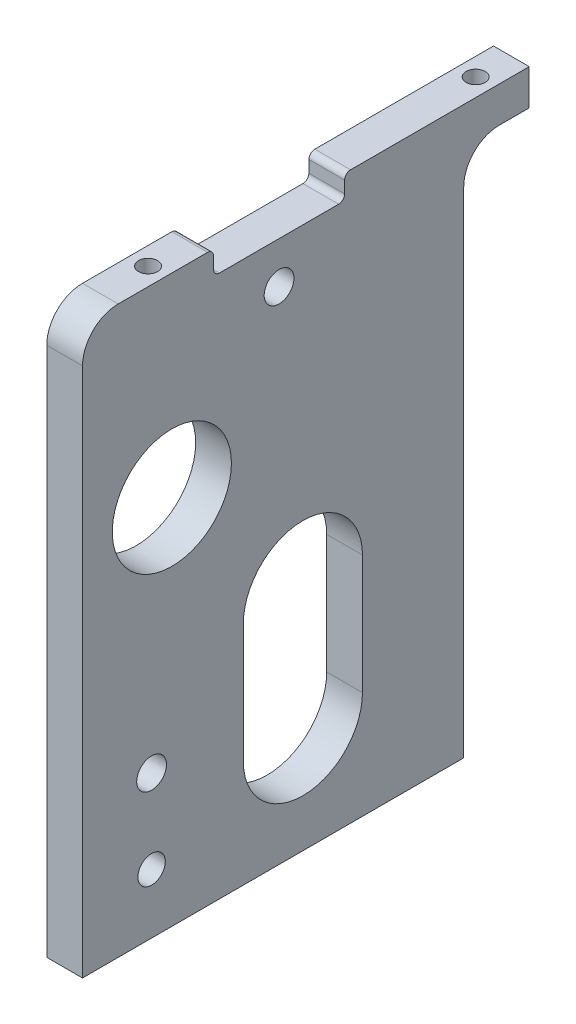
SolidWorks part; units mm, degrees
material "6063-T5"
ref_plane "Front Plane" through (0, 0, 0) normal (0, 0, 1) x (1, 0, 0)
ref_plane "Top Plane" through (0, 0, 0) normal (0, 1, 0) x (1, 0, 0)
ref_plane "Right Plane" through (0, 0, 0) normal (1, 0, 0) x (0, 0, -1)
sketch "Sketch1" plane through (0, 0, 0) normal (1, 0, 0) x (0, 0, -1)
  line L0 (-15.5, -23.75) -> (22, -23.75) construction
  line L1 (22, -23.75) -> (22, 16.25) construction
  line L2 (15.5, 23.75) -> (-15.5, 23.75) construction
  line L3 (-15.5, 23.75) -> (-15.5, -23.75) construction
  line L4 (55, 0) -> (-55, 0) construction
  line L5 (2, -4.75) -> (2, -14.75) construction
  line L6 (7, -4.75) -> (7, -14.75)
  line L7 (-3, -4.75) -> (-3, -14.75)
  line L8 (0, 55) -> (0, -55) construction
  line L9 (-15.5, 23.75) -> (15.5, 23.75)
  line L10 (15.5, 8.25) -> (15.5, -23.75)
  line L11 (-15.5, -23.75) -> (15.5, -23.75)
  line L12 (22, 23.75) -> (22, 16.25) construction
  line L13 (15.5, 8.25) -> (15.5, 20.75)
  line L14 (22, 23.75) -> (15.5, 23.75) construction
  line L15 (15.5, 23.75) -> (22, 23.75) construction
  line L16 (22, 16.25) -> (22, 23.75) construction
  line L17 (15.5, 23.75) -> (21, 23.75)
  line L18 (21, 23.75) -> (21, 20.75)
  line L19 (21, 20.75) -> (15.5, 20.75)
  line L20 (15.5, 20.75) -> (15.5, 23.75) construction
  line L21 (-15.5, -23.75) -> (-16.5, -23.75)
  line L28 (-16.5, -23.75) -> (-16.5, 23.75)
  line L29 (-16.5, 23.75) -> (-15.5, 23.75)
  arc A0 (7, -4.75) -> (-3, -4.75) centre (2, -4.75) ccw
  arc A1 (-3, -14.75) -> (7, -14.75) centre (2, -14.75) ccw
  arc A3 (15.5, 8.25) -> (18, 12.25) centre (21.4284, 7.326) cw construction
  arc A4 (18, 12.25) -> (22, 16.25) centre (16.2583, 17.9917) ccw construction
  circle A5 centre (-9, 7.422) radius 5
  circle A6 centre (-10.7, -18.75) radius 1.15
  point P2 (0, 23.75)
  point P5 (-15.5, 0)
  point P11 (2, -9.75)
  dimension "D12" = 6
  dimension "D14" = 10
  dimension "D21" = 2.3
  dimension "D1" = 47.5
  dimension "D2" = 37.5
  dimension "D3" = 10
  dimension "D4" = 10
  dimension "D5" = 0
  dimension "D7" = 17.5
  dimension "D8" = 31
  dimension "D9" = 8
  dimension "D10" = 4
  dimension "D11" = 2.5
  dimension "D13" = 32
  dimension "D15" = 31.172
  dimension "D16" = 6.5
  dimension "D6" = 19
  dimension "D17" = 5.5
  dimension "D18" = 3
  dimension "D19" = 4.8
  dimension "D20" = 5
  dimension "D24" = 1
extrude "Boss-Extrude1" add sketch "Sketch1" along normal mid plane 3
sketch "Sketch2" plane through (-1.5, 0, 0) normal (-1, 0, 0) x (0, 0, 1)
  line L0 (-21, 23.75) -> (16.5, 23.75) construction
  line L1 (5.5, 23.75) -> (12.5, 23.75)
  line L2 (5.5, 23.75) -> (5.5, 20.75)
  line L3 (5.5, 20.75) -> (12.5, 20.75)
  line L4 (12.5, 23.75) -> (12.5, 20.75)
  line L10 (16.5, 23.75) -> (16.5, -23.75) construction
  line L11 (-21, 23.75) -> (-14, 23.75)
  line L12 (-21, 23.75) -> (-21, 20.75)
  line L13 (-21, 20.75) -> (-14, 20.75)
  line L14 (-14, 23.75) -> (-14, 20.75)
  dimension "D1" = 4
  dimension "D2" = 3
  dimension "D3" = 7
extrude "Boss-Extrude2" [suppressed] add sketch "Sketch2" along normal blind 8
sketch "Sketch3" [suppressed] plane through (0, 20.75, 0) normal (0, 1, 0) x (1, 0, 0)
  line L0 (-1.5, -5.5) -> (-1.5, -12.5) construction
  line L7 (-5, 20.0981) -> (-7.25, 18.799)
  line L8 (-7.25, 18.799) -> (-7.25, 16.201)
  line L9 (-7.25, 16.201) -> (-5, 14.9019)
  line L10 (-5, 14.9019) -> (-2.75, 16.201)
  line L11 (-2.75, 16.201) -> (-2.75, 18.799)
  line L12 (-2.75, 18.799) -> (-5, 20.0981)
  line L13 (1.5, -16.5) -> (-1.5, -16.5) construction
  line L14 (-1.5, 15.5) -> (-1.5, 14) construction
  line L15 (1.5, 15.5) -> (-1.5, 15.5) construction
  line L16 (-9.5, -5.5) -> (-9.5, -12.5) construction
  line L18 (-7.25, -7.701) -> (-7.25, -10.299)
  line L19 (-7.25, -10.299) -> (-5, -11.5981)
  line L20 (-5, -11.5981) -> (-2.75, -10.299)
  line L21 (-2.75, -10.299) -> (-2.75, -7.701)
  line L22 (-2.75, -7.701) -> (-5, -6.4019)
  line L23 (-5, -6.4019) -> (-7.25, -7.701)
  circle A0 centre (-5, -9) radius 2.25 construction
  circle A1 centre (-5, 17.5) radius 2.25 construction
  dimension "D1" = 4.5
  dimension "D2" = 3.5
  dimension "D3" = 7.5
  dimension "D4" = 2
  dimension "D5" = 3.5
extrude "Cut-Extrude1" [suppressed] cut sketch "Sketch3" along normal blind 2
fillet "Fillet1" radius 3 2 edges at (0, 20.75, -15.5) (0, 23.75, 16.5)
hole_wizard "M2 Clearance Hole1" [suppressed] positions "Sketch4" profile "Sketch5" hole size "M2" standard "ISO"
sketch "Sketch4" [suppressed] plane through (0, 22.75, 0) normal (0, -1, 0) x (-1, 0, 0)
  line L4 (1.5, 18.5) -> (1.5, 14) construction
  line L5 (1.5, -5.5) -> (1.5, -12.5) construction
  line L6 (1.5, 15.5) -> (-1.5, 15.5) construction
  line L8 (-1.5, -16.5) -> (1.5, -16.5) construction
  point P0 (5, -9)
  point P13 (5, 17.5)
  dimension "D1" = 3.5
  dimension "D3" = 3.5
  dimension "D2" = 2
  dimension "D4" = 7.5
sketch "Sketch5" plane through (-5, 22.75, 9) normal (1, 0, 0) x (0, 0, -1)
  line L0 (0, 0) -> (0, 8.9811)
  line L1 (0, 8.9811) -> (1.3, 8.2)
  line L2 (1.3, 8.2) -> (1.3, 0)
  line L5 (1.3, 0) -> (0, 0)
  line L10 (0, 8.9811) -> (-1.3, 8.2) construction
  line L11 (0, -6.35) -> (0, 107.95) construction
  dimension "Hole Dia." = 2.6
  dimension "Hole Depth" = 8.2
  dimension "Drill Angle" = 118
fillet "Fillet2" [suppressed] radius 1.5
hole_wizard "Tap Drill for M2 Tap1" positions "Sketch6" profile "Sketch7" hole size "M2" standard "ISO"
sketch "Sketch6" plane through (0, 23.75, 0) normal (0, 1, 0) x (1, 0, 0)
  line L0 (1.5, 21) -> (-1.5, 21) construction
  line L1 (1.5, 21) -> (1.5, -13.5) construction
  point P0 (0, -9.5)
  point P2 (0, 18)
  dimension "D1" = 3
  dimension "D2" = 1.5
  dimension "D3" = 27.5
sketch "Sketch7" plane through (0, 23.75, 9.5) normal (1, 0, 0) x (0, 0, 1)
  line L0 (0, 0) -> (0, 6.4807)
  line L1 (0, 6.4807) -> (0.8, 6)
  line L2 (0.8, 6) -> (0.8, 0)
  line L5 (0.8, 0) -> (0, 0)
  line L10 (0, 6.4807) -> (-0.8, 6) construction
  line L11 (0, -6.35) -> (0, 107.95) construction
  dimension "Hole Dia." = 1.6
  dimension "Hole Depth" = 6
  dimension "Drill Angle" = 118
cosmetic thread "Cosmetic Thread1" parameters "D2"=2
cosmetic thread "Cosmetic Thread2" parameters "D2"=2
hole_wizard "Tap Drill for M3 Tap1" positions "Sketch8" profile "Sketch9" hole size "M3" standard "ISO" end condition through all
sketch "Sketch8" plane through (1.5, 0, 0) normal (1, 0, 0) x (0, 0, -1)
  line L0 (-16.5, -23.75) -> (15.5, -23.75) construction
  line L1 (21, 23.75) -> (-13.5, 23.75) construction
  line L2 (-16.5, 20.75) -> (-16.5, -23.75) construction
  point P0 (-10.7, -11.75)
  point P2 (0, 18.25)
  dimension "D1" = 12
  dimension "D2" = 5.5
  dimension "D3" = 5.8
  dimension "D4" = 16.5
sketch "Sketch9" plane through (1.5, -11.75, 10.7) normal (0, 1, 0) x (0, 0, -1)
  line L0 (0, 0) -> (0, 3)
  line L1 (0, 3) -> (1.25, 3)
  line L2 (1.25, 3) -> (1.25, 0)
  line L5 (1.25, 0) -> (0, 0)
  line L11 (0, -6.35) -> (0, 107.95) construction
  dimension "Thru Hole Dia." = 2.5
  dimension "Thru Hole Depth" = 3
cosmetic thread "Cosmetic Thread3" parameters "D2"=3
cosmetic thread "Cosmetic Thread4" parameters "D2"=3
sketch "Sketch10" plane through (1.5, 0, 0) normal (1, 0, 0) x (0, 0, -1)
  line L0 (21, 23.75) -> (-13.5, 23.75) construction
  line L1 (-5.5, 23.75) -> (5.5, 23.75)
  line L2 (-5.5, 23.75) -> (-5.5, 21.75)
  line L3 (-5.5, 21.75) -> (5.5, 21.75)
  line L4 (5.5, 23.75) -> (5.5, 21.75)
  line L6 (-16.5, 20.75) -> (-16.5, -23.75) construction
  point P6 (0, 23.75)
  dimension "D1" = 16.5
  dimension "D2" = 2
  dimension "D3" = 11
extrude "Cut-Extrude2" cut sketch "Sketch10" against normal through all
fillet "Fillet3" radius 0.5 4 edges at (0, 21.75, 5.5) (0, 23.75, 5.5) (0, 23.75, -5.5) (0, 21.75, -5.5)
equation "\"D_bottom_ground\"= 6.405"
equation "\"Thickness_bottom\"= 3"
equation "\"H_Front\"=3"
equation "\"R_dribbler\"= 7"
equation "\"H_dribbler\"= 43.577"
equation "\"D15@Sketch1\"=\"H_dribbler\"-\"D_bottom_ground\"-\"Thickness_bottom\"-\"H_Front\""
equation "\"D1@Sketch4\"=\"D3@Sketch4\""
